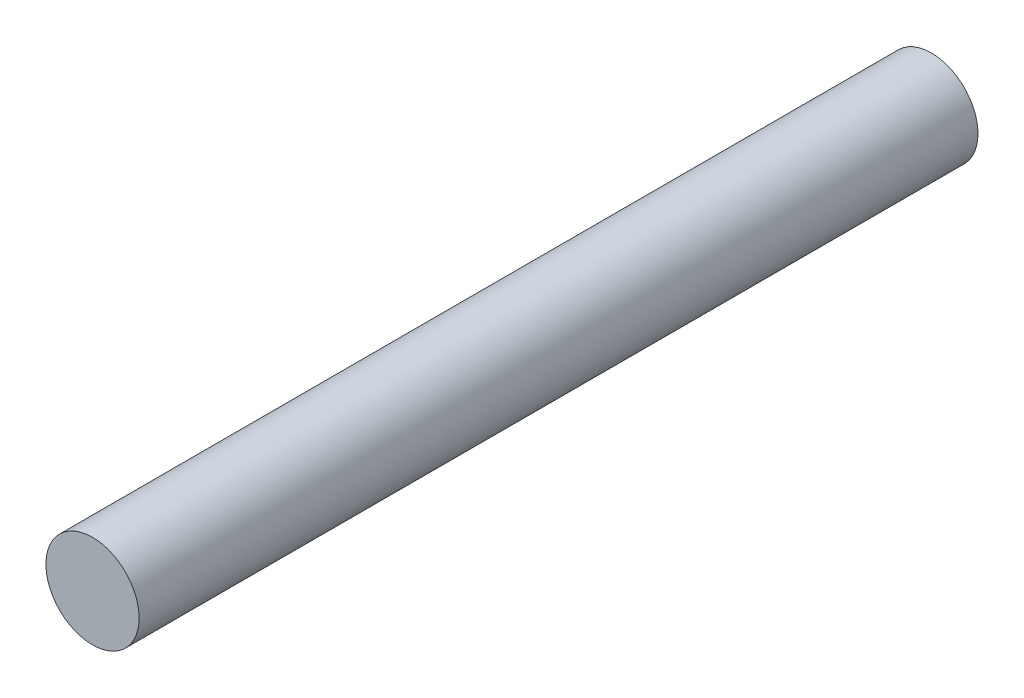
SolidWorks part; units mm, degrees
material "AISI 1020"
ref_plane "Plano frontal" through (0, 0, 0) normal (0, 0, 1) x (1, 0, 0)
ref_plane "Plano superior" through (0, 0, 0) normal (0, 1, 0) x (1, 0, 0)
ref_plane "Plano direito" through (0, 0, 0) normal (1, 0, 0) x (0, 0, -1)
sketch "Esboço1" plane through (0, 0, 0) normal (0, 0, 1) x (1, 0, 0)
  circle A0 centre (0, 0) radius 5
  dimension "D1" = 10
extrude "Ressalto-extrusão1" add sketch "Esboço1" against normal blind 90
